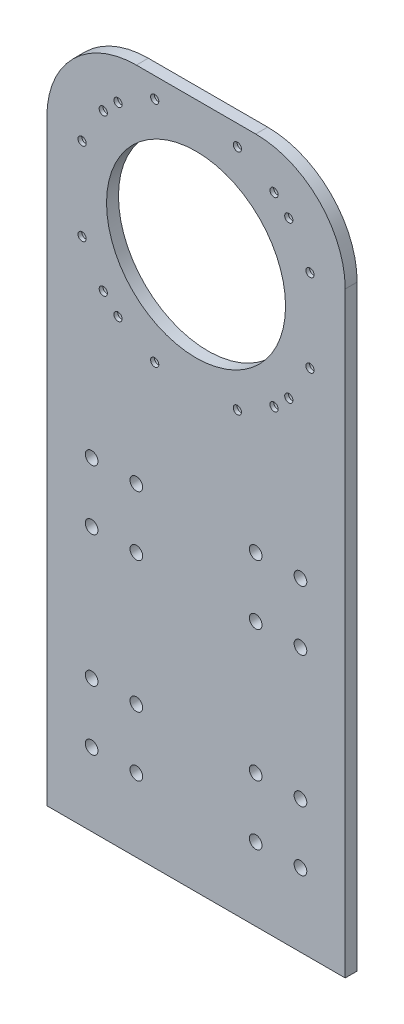
SolidWorks part; units mm, degrees
ref_plane "前视基准面" through (0, 0, 0) normal (0, 0, 1) x (1, 0, 0)
ref_plane "上视基准面" through (0, 0, 0) normal (0, 1, 0) x (1, 0, 0)
ref_plane "右视基准面" through (0, 0, 0) normal (1, 0, 0) x (0, 0, -1)
other "Configuration Table"
sketch "草图1" plane through (0, 0, 0) normal (0, 0, 1) x (1, 0, 0)
  line L0 (0, 0) -> (0, 498.031) construction
  line L1 (100, 0) -> (-100, 0)
  line L2 (-100, 0) -> (-100, 460)
  line L3 (-100, 460) -> (100, 460)
  line L4 (100, 0) -> (100, 460)
  point P7 (0, 460)
  dimension "D1" = 460
  dimension "D2" = 100
extrude "凸台-拉伸1" add sketch "草图1" along normal blind 8
sketch "草图2" plane through (0, 0, 0) normal (0, 0, -1) x (-1, 0, 0)
  line L0 (100, 0) -> (-100, 0) construction
  circle A0 centre (0, 370) radius 60
  circle A1 centre (0, 370) radius 81.25 construction
  dimension "D1" = 120
  dimension "D3" = 162.5
  dimension "D2" = 370
extrude "切除-拉伸1" cut sketch "草图2" against normal blind 10
fillet "圆角1" radius 60 2 edges at (-100, 460, 4) (100, 460, 4)
sketch "草图3" plane through (0, 0, 8) normal (0, 0, 1) x (1, 0, 0)
  arc A0 (73.8802, 397.7062) -> (78.8802, 397.7062) centre (76.3802, 397.7062) ccw construction
  arc A1 (73.8802, 342.2938) -> (78.8802, 342.2938) centre (76.3802, 342.2938) ccw construction
  arc A6 (59.6844, 317.7059) -> (64.6844, 317.7059) centre (62.1844, 317.7059) ccw construction
  arc A7 (49.7941, 307.8156) -> (54.7941, 307.8156) centre (52.2941, 307.8156) ccw construction
  arc A8 (25.2062, 293.6198) -> (30.2062, 293.6198) centre (27.7062, 293.6198) ccw construction
  arc A9 (-30.2062, 293.6198) -> (-25.2062, 293.6198) centre (-27.7062, 293.6198) ccw construction
  arc A10 (-54.7941, 307.8156) -> (-49.7941, 307.8156) centre (-52.2941, 307.8156) ccw construction
  arc A11 (-64.6844, 317.7059) -> (-59.6844, 317.7059) centre (-62.1844, 317.7059) ccw construction
  arc A12 (-78.8802, 342.2938) -> (-73.8802, 342.2938) centre (-76.3802, 342.2938) ccw construction
  arc A13 (-78.8802, 397.7062) -> (-73.8802, 397.7062) centre (-76.3802, 397.7062) ccw construction
  arc A14 (-64.6844, 422.2941) -> (-59.6844, 422.2941) centre (-62.1844, 422.2941) ccw construction
  arc A15 (-54.7941, 432.1844) -> (-49.7941, 432.1844) centre (-52.2941, 432.1844) ccw construction
  arc A16 (-30.2062, 446.3802) -> (-25.2062, 446.3802) centre (-27.7062, 446.3802) ccw construction
  arc A17 (25.2062, 446.3802) -> (30.2062, 446.3802) centre (27.7062, 446.3802) ccw construction
  arc A18 (49.7941, 432.1844) -> (54.7941, 432.1844) centre (52.2941, 432.1844) ccw construction
  arc A19 (59.6844, 422.2941) -> (64.6844, 422.2941) centre (62.1844, 422.2941) ccw construction
  arc A20 (73.8802, 397.7062) -> (78.8802, 397.7062) centre (76.3802, 397.7062) ccw construction
  arc A21 (73.8802, 342.2938) -> (78.8802, 342.2938) centre (76.3802, 342.2938) ccw construction
  arc A22 (59.6844, 317.7059) -> (64.6844, 317.7059) centre (62.1844, 317.7059) ccw construction
  arc A23 (49.7941, 307.8156) -> (54.7941, 307.8156) centre (52.2941, 307.8156) ccw construction
  arc A24 (25.2062, 293.6198) -> (30.2062, 293.6198) centre (27.7062, 293.6198) ccw construction
  arc A25 (-30.2062, 293.6198) -> (-25.2062, 293.6198) centre (-27.7062, 293.6198) ccw construction
  arc A26 (-54.7941, 307.8156) -> (-49.7941, 307.8156) centre (-52.2941, 307.8156) ccw construction
  arc A27 (-64.6844, 317.7059) -> (-59.6844, 317.7059) centre (-62.1844, 317.7059) ccw construction
  arc A28 (-78.8802, 342.2938) -> (-73.8802, 342.2938) centre (-76.3802, 342.2938) ccw construction
  arc A29 (-78.8802, 397.7062) -> (-73.8802, 397.7062) centre (-76.3802, 397.7062) ccw construction
  arc A30 (-64.6844, 422.2941) -> (-59.6844, 422.2941) centre (-62.1844, 422.2941) ccw construction
  arc A31 (-54.7941, 432.1844) -> (-49.7941, 432.1844) centre (-52.2941, 432.1844) ccw construction
  arc A32 (-30.2062, 446.3802) -> (-25.2062, 446.3802) centre (-27.7062, 446.3802) ccw construction
  arc A33 (25.2062, 446.3802) -> (30.2062, 446.3802) centre (27.7062, 446.3802) ccw construction
  arc A34 (49.7941, 432.1844) -> (54.7941, 432.1844) centre (52.2941, 432.1844) ccw construction
  arc A35 (59.6844, 422.2941) -> (64.6844, 422.2941) centre (62.1844, 422.2941) ccw construction
  circle A36 centre (27.7062, 446.3802) radius 2.75
  circle A37 centre (52.2941, 432.1844) radius 2.75
  circle A38 centre (62.1844, 422.2941) radius 2.75
  circle A39 centre (76.3802, 397.7062) radius 2.75
  circle A40 centre (76.3802, 342.2938) radius 2.75
  circle A41 centre (62.1844, 317.7059) radius 2.75
  circle A42 centre (52.2941, 307.8156) radius 2.75
  circle A43 centre (27.7062, 293.6198) radius 2.75
  circle A44 centre (-27.7062, 293.6198) radius 2.75
  circle A45 centre (-52.2941, 307.8156) radius 2.75
  circle A46 centre (-62.1844, 317.7059) radius 2.75
  circle A47 centre (-76.3802, 342.2938) radius 2.75
  circle A48 centre (-76.3802, 397.7062) radius 2.75
  circle A49 centre (-62.1844, 422.2941) radius 2.75
  circle A50 centre (-52.2941, 432.1844) radius 2.75
  circle A51 centre (-27.7062, 446.3802) radius 2.75
  dimension "D1" = 5.5
extrude "切除-拉伸2" cut sketch "草图3" against normal blind 10
sketch "草图4" plane through (0, 0, 0) normal (0, 0, -1) x (-1, 0, 0)
  circle A0 centre (27.7062, 446.3802) radius 6
  circle A1 centre (52.2941, 432.1844) radius 6
  circle A2 centre (62.1844, 422.2941) radius 6
  circle A3 centre (76.3802, 397.7062) radius 6
  circle A4 centre (76.3802, 342.2938) radius 6
  circle A5 centre (62.1844, 317.7059) radius 6
  circle A6 centre (52.2941, 307.8156) radius 6
  circle A7 centre (27.7062, 293.6198) radius 6
  circle A8 centre (-27.7062, 293.6198) radius 6
  circle A9 centre (-52.2941, 307.8156) radius 6
  circle A10 centre (-62.1844, 317.7059) radius 6
  circle A11 centre (-76.3802, 342.2938) radius 6
  circle A12 centre (-76.3802, 397.7062) radius 6
  circle A13 centre (-62.1844, 422.2941) radius 6
  circle A14 centre (-52.2941, 432.1844) radius 6
  circle A15 centre (-27.7062, 446.3802) radius 6
  dimension "D1" = 12
extrude "切除-拉伸3" cut sketch "草图4" against normal blind 5.5
sketch "草图5" plane through (0, 0, 0) normal (0, 0, -1) x (-1, 0, 0)
  line L0 (0, 0) -> (0, 253.7158) construction
  line L1 (19.0341, 30) -> (84.0165, 30) construction
  line L2 (84.0165, 236) -> (19.0341, 236) construction
  line L3 (84.0165, 108) -> (19.0341, 108) construction
  line L4 (100, 0) -> (-100, 0) construction
  line L5 (-84.0165, 108) -> (-19.0341, 108) construction
  line L6 (-84.0165, 236) -> (-19.0341, 236) construction
  line L7 (-19.0341, 30) -> (-84.0165, 30) construction
  circle A0 centre (40, 49) radius 4.25
  circle A1 centre (70, 49) radius 4.25
  circle A2 centre (40, 89) radius 4.25
  circle A3 centre (70, 89) radius 4.25
  circle A4 centre (40, 217) radius 4.25
  circle A5 centre (70, 177) radius 4.25
  circle A6 centre (40, 177) radius 4.25
  circle A7 centre (70, 217) radius 4.25
  circle A8 centre (-70, 217) radius 4.25
  circle A9 centre (-40, 177) radius 4.25
  circle A10 centre (-70, 177) radius 4.25
  circle A11 centre (-40, 217) radius 4.25
  circle A12 centre (-70, 89) radius 4.25
  circle A13 centre (-40, 89) radius 4.25
  circle A14 centre (-70, 49) radius 4.25
  circle A15 centre (-40, 49) radius 4.25
  dimension "D1" = 8.5
  dimension "D2" = 30
  dimension "D3" = 19
  dimension "D4" = 40
  dimension "D5" = 30
  dimension "D6" = 78
  dimension "D7" = 19
  dimension "D8" = 2
extrude "切除-拉伸4" cut sketch "草图5" against normal blind 10
